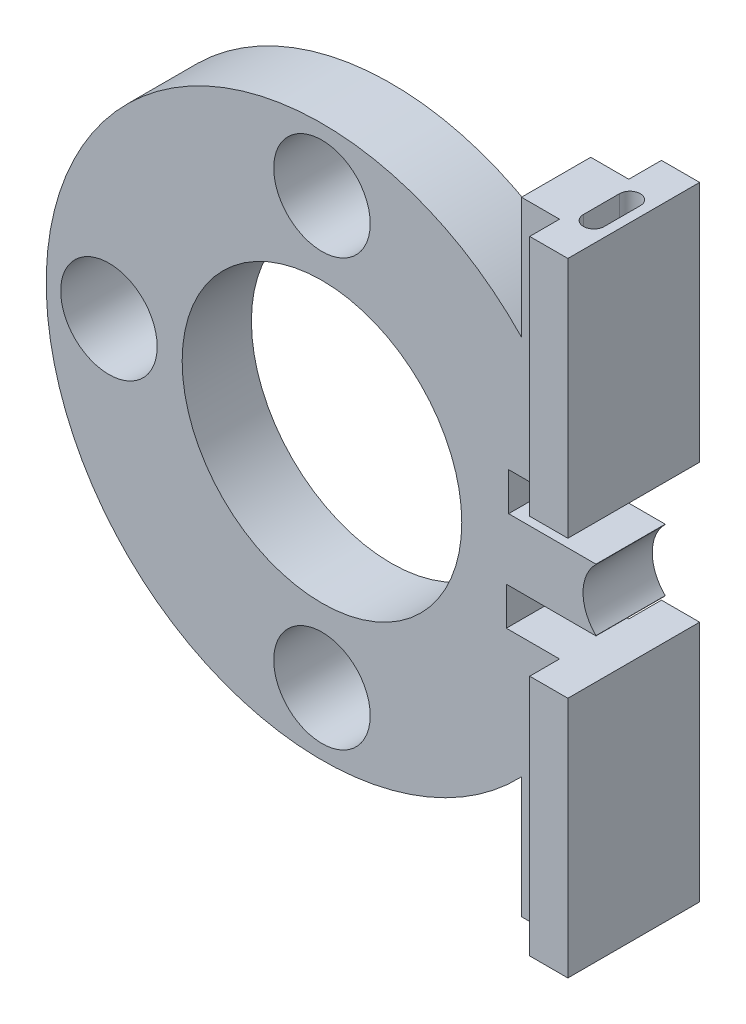
SolidWorks part; units mm, degrees
ref_plane "前视基准面" through (0, 0, 0) normal (0, 0, 1) x (1, 0, 0)
ref_plane "上视基准面" through (0, 0, 0) normal (0, 1, 0) x (1, 0, 0)
ref_plane "右视基准面" through (0, 0, 0) normal (1, 0, 0) x (0, 0, -1)
sketch "草图1" plane through (0, 0, 0) normal (0, 0, 1) x (1, 0, 0)
  circle A0 centre (0, 0) radius 39.8271
  circle A1 centre (0, 0) radius 20.1923
  circle A2 centre (0, 30.7696) radius 6.9684
  circle A4 centre (0, -30.7696) radius 6.9684
  circle A5 centre (-30.7696, 0) radius 6.9684
  circle A6 centre (30.7696, 0) radius 6.9684 [skipped]
  point P15 (0, 0)
  dimension "D1" = 4
extrude "凸台-拉伸1" add sketch "草图1" along normal blind 10
ref_plane "基准面1" through (0, 20, 0) normal (0, 1, 0) x (1, 0, 0)
ref_plane "基准面2" through (0, -20, 0) normal (0, 1, 0) x (1, 0, 0)
sketch "草图9" plane through (0, 20, 0) normal (0, 1, 0) x (1, 0, 0)
  line L0 (39.8242, -14.3094) -> (34.3112, -14.3094)
  line L1 (39.8242, -14.3094) -> (39.8242, 4.7198)
  line L2 (39.8242, 4.7198) -> (34.3112, 4.7198)
  line L3 (34.3112, -14.3094) -> (34.3112, 4.7198)
  line L4 (34.3112, 0) -> (28.8171, 0)
  line L5 (34.3112, -10) -> (28.8171, -10)
  line L6 (28.8171, 0) -> (28.8171, -10)
  line L7 (36.9521, -2.4757) -> (36.9521, -7.6855) construction
  line L8 (38.4566, -2.4757) -> (38.4566, -7.6855)
  line L9 (35.4477, -2.4757) -> (35.4477, -7.6855)
  arc A0 (38.4566, -2.4757) -> (35.4477, -2.4757) centre (36.9521, -2.4757) ccw
  arc A1 (35.4477, -7.6855) -> (38.4566, -7.6855) centre (36.9521, -7.6855) ccw
  point P10 (36.9521, -5.0806)
sketch "草图10" plane through (0, -20, 0) normal (0, 1, 0) x (1, 0, 0)
  line L0 (39.8242, -14.3095) -> (34.3113, -14.3095)
  line L1 (39.8242, -14.3095) -> (39.8242, 4.7198)
  line L2 (39.8242, 4.7198) -> (34.3113, 4.7198)
  line L3 (34.3113, -14.3095) -> (34.3113, 4.7198)
  line L4 (34.3113, 0) -> (28.8172, 0)
  line L5 (34.3113, -10) -> (28.8172, -10)
  line L6 (28.8172, 0) -> (28.8172, -10)
  line L7 (36.9522, -2.4757) -> (36.9522, -7.6855) construction
  line L8 (38.4566, -2.4757) -> (38.4566, -7.6855)
  line L9 (35.4478, -2.4757) -> (35.4478, -7.6855)
  arc A0 (38.4566, -2.4757) -> (35.4478, -2.4757) centre (36.9522, -2.4757) ccw
  arc A1 (35.4478, -7.6855) -> (38.4566, -7.6855) centre (36.9522, -7.6855) ccw
  point P10 (36.9522, -5.0806)
extrude "凸台-拉伸4" add sketch "草图9" along normal blind 25 and the other way blind 10 contours L3 L0 L1 L2 A1 L9 A0 L8 | L4 L6 L5 L3
extrude "凸台-拉伸5" add sketch "草图10" along normal blind 10 and the other way blind 25 contours L3 L0 L1 L2 A1 L9 A0 L8 | L4 L6 L5 L3
sketch "草图11" plane through (0, 0, 0) normal (0, 0, 1) x (1, 0, 0)
  line L0 (26.6251, -4.494) -> (43.9175, -4.494)
  line L1 (26.9591, 9.9983) -> (44.2514, 9.9983)
  line L2 (26.9591, 9.9983) -> (26.9591, 4.4861)
  line L3 (26.9591, 4.4861) -> (44.2514, 4.4861)
  line L4 (44.2514, 9.9983) -> (44.2514, 4.4861)
  line L5 (26.6251, -4.494) -> (26.6251, -10.0062)
  line L6 (26.6251, -10.0062) -> (43.9175, -10.0062)
  line L7 (43.9175, -4.494) -> (43.9175, -10.0062)
  line L8 (10.4661, 0) -> (-10.4661, 0) construction
  circle A0 centre (43.9175, 0) radius 6.2158
extrude "切除-拉伸3" cut sketch "草图11" against normal blind 30 and the other way blind 30 contours L3 A0 L0 L7 L4 | A0 L4 L1 L2 L3 | A0 L0 L5 L6 L7
sketch "草图6" plane through (0, 0, 0) normal (0, 1, 0) x (1, 0, 0)
